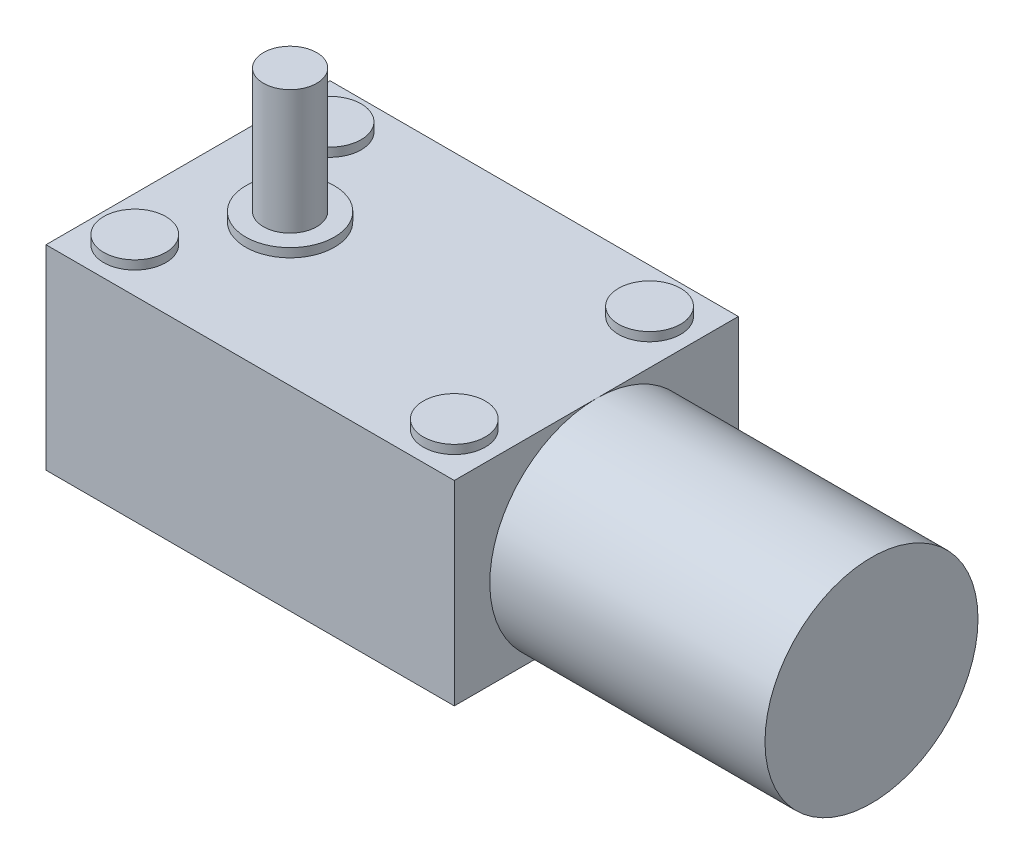
SolidWorks part; units mm, degrees
ref_plane "Спереди" through (0, 0, 0) normal (0, 0, 1) x (1, 0, 0)
ref_plane "Сверху" through (0, 0, 0) normal (0, 1, 0) x (1, 0, 0)
ref_plane "Справа" through (0, 0, 0) normal (1, 0, 0) x (0, 0, -1)
sketch "Эскиз1" plane through (0, 0, 0) normal (0, 1, 0) x (1, 0, 0)
  line L1 (-23, -16) -> (23, -16)
  line L2 (-23, -16) -> (-23, 16)
  line L3 (-23, 16) -> (23, 16)
  line L4 (23, -16) -> (23, 16)
  line L5 (-23, -16) -> (23, 16) construction
  line L6 (-23, 16) -> (23, -16) construction
  point P0 (0, 0)
  dimension "D1" = 46
  dimension "D2" = 32
extrude "Бобышка-Вытянуть1" add sketch "Эскиз1" along normal blind 22
sketch "Эскиз2" plane through (23, 0, 0) normal (1, 0, 0) x (0, 0, -1)
  line L0 (-16, 22) -> (16, 22) construction
  circle A0 centre (0, 10) radius 12
  dimension "D1" = 24
  dimension "D2" = 12
extrude "Бобышка-Вытянуть2" add sketch "Эскиз2" along normal blind 31
sketch "Эскиз3" plane through (0, 22, 0) normal (0, 1, 0) x (1, 0, 0)
  circle A0 centre (-11.5, 0) radius 5
  dimension "D1" = 10
  dimension "D2" = 11.5
extrude "Бобышка-Вытянуть3" add sketch "Эскиз3" along normal blind 1
sketch "Эскиз4" plane through (0, 23, 0) normal (0, 1, 0) x (1, 0, 0)
  circle A0 centre (-11.5, 0) radius 3
  dimension "D1" = 6
extrude "Бобышка-Вытянуть4" add sketch "Эскиз4" along normal blind 14
sketch "Эскиз5" plane through (0, 22, 0) normal (0, 1, 0) x (1, 0, 0)
  line L0 (-23, 16) -> (-23, -16) construction
  line L1 (23, 16) -> (-23, 16) construction
  line L2 (23, 0) -> (23, 12) construction
  line L3 (-23, -16) -> (23, -16) construction
  circle A0 centre (18, 11) radius 3.5
  circle A1 centre (18, -11) radius 3.5
  circle A2 centre (-18, -11) radius 3.5
  circle A3 centre (-18, 11) radius 3.5
  point P8 (0, 0)
  dimension "D1" = 7
  dimension "D2" = 5
  dimension "D3" = 5
  dimension "D4" = 5
  dimension "D5" = 5
extrude "Бобышка-Вытянуть5" add sketch "Эскиз5" along normal blind 1
